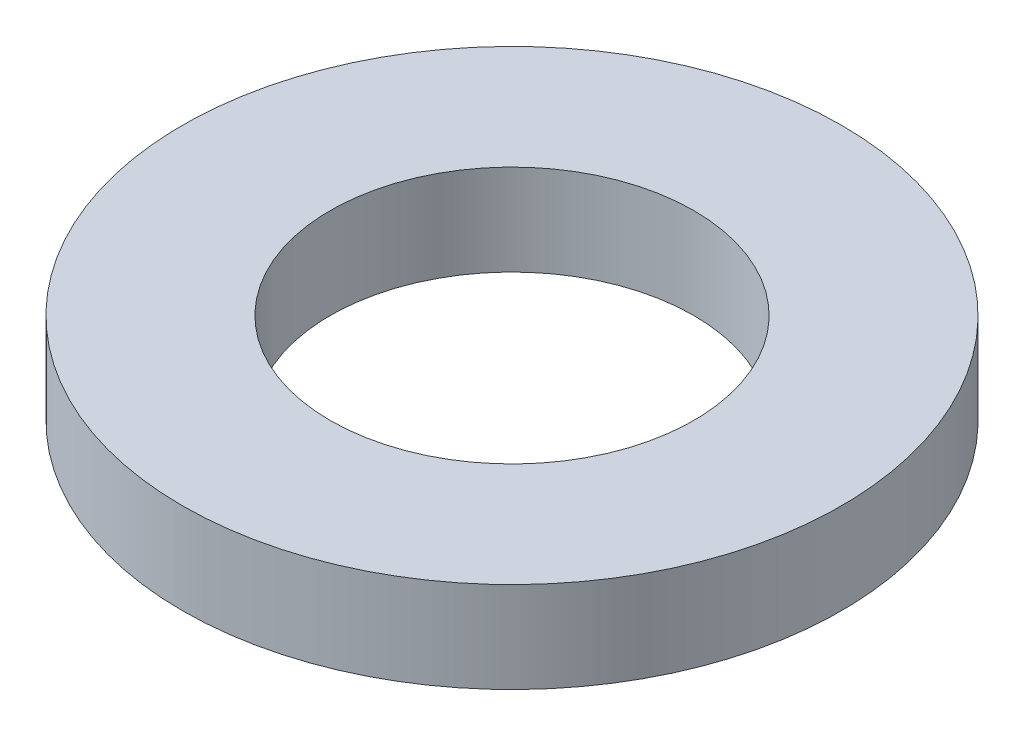
SolidWorks part; units mm, degrees
ref_plane "前视基准面" through (0, 0, 0) normal (0, 0, 1) x (1, 0, 0)
ref_plane "上视基准面" through (0, 0, 0) normal (0, 1, 0) x (1, 0, 0)
ref_plane "右视基准面" through (0, 0, 0) normal (1, 0, 0) x (0, 0, -1)
sketch "草图1" plane through (0, 0, 0) normal (0, 1, 0) x (1, 0, 0)
  circle A0 centre (0, 0) radius 1.6
  circle A1 centre (0, 0) radius 2.9
  dimension "D1" = 3.2
  dimension "D2" = 5.8
extrude "凸台-拉伸1" add sketch "草图1" along normal blind 0.8
